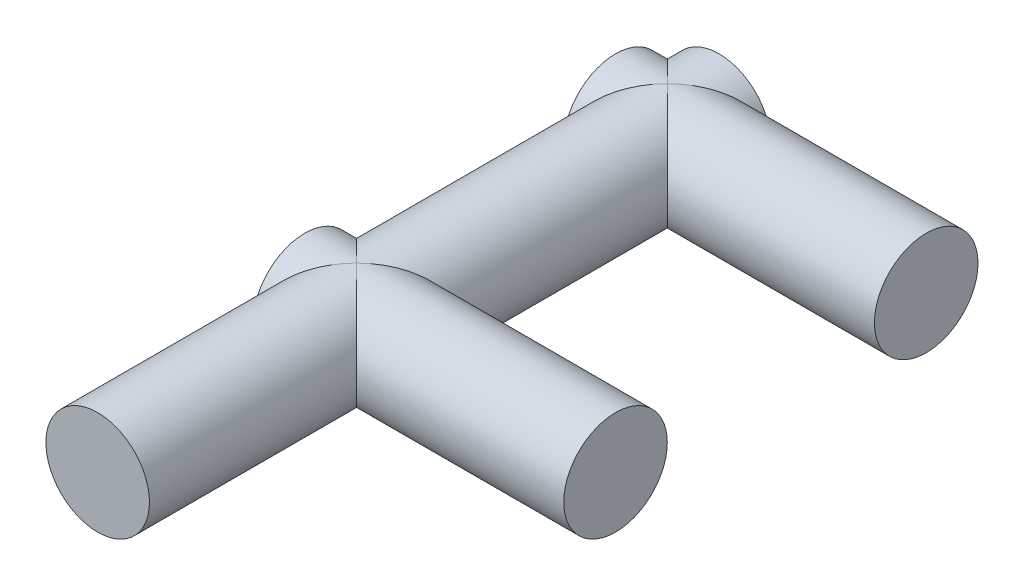
SolidWorks part; units mm, degrees
ref_plane "Front Plane" through (0, 0, 0) normal (0, 0, 1) x (1, 0, 0)
ref_plane "Top Plane" through (0, 0, 0) normal (0, 1, 0) x (1, 0, 0)
ref_plane "Right Plane" through (0, 0, 0) normal (1, 0, 0) x (0, 0, -1)
sketch "Sketch3" plane through (0, 0, 0) normal (1, 0, 0) x (0, 0, -1)
  line L0 (-1.1906, 0) -> (1.1906, 0) construction
  circle A0 centre (-1.1906, 0) radius 0.3969
  circle A1 centre (1.1906, 0) radius 0.3969
  point P4 (0, 0)
  point P6 (0.7937, 0)
  point P7 (-0.7938, 0)
  dimension "D1" = 0.7937
  dimension "D2" = 1.5875
extrude "Boss-Extrude2" add sketch "Sketch3" along normal blind 2.3812
sketch "Sketch4" plane through (0, 0, 0) normal (0, 0, 1) x (1, 0, 0)
  line L0 (0, 0.3969) -> (0, -0.3969) construction
  circle A0 centre (0.3969, 0) radius 0.3969
  point P4 (0.3969, 0.0843)
  dimension "D1" = 0.7937
extrude "Boss-Extrude3" add sketch "Sketch4" along normal blind 3.175 and the other way blind 1.5875
